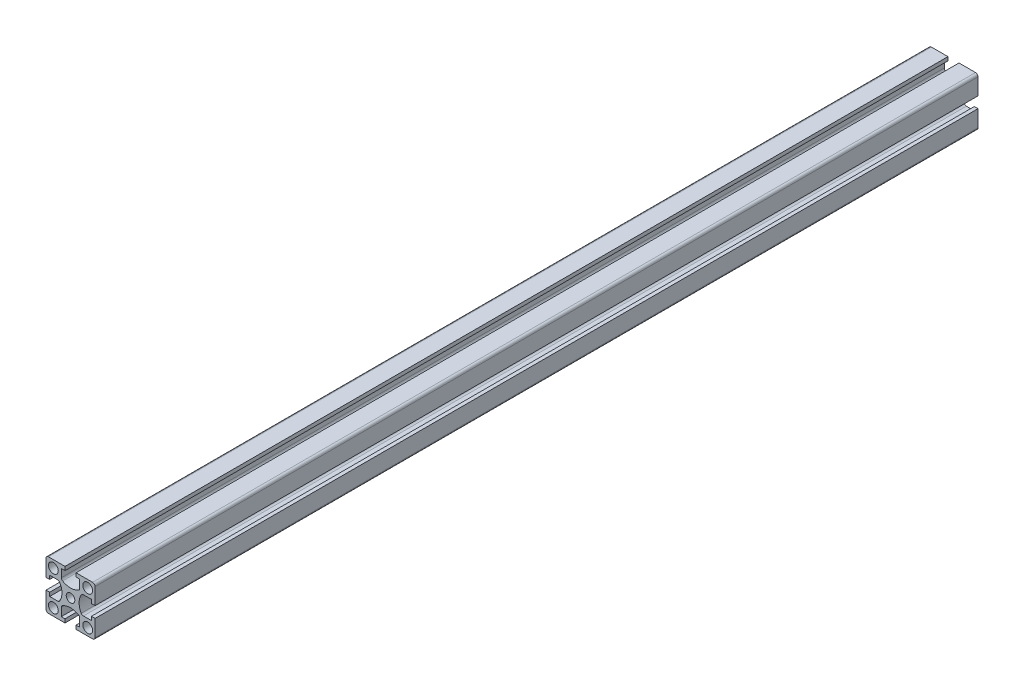
SolidWorks part; units mm, degrees
ref_plane "Front Plane" through (0, 0, 0) normal (0, 0, 1) x (1, 0, 0)
ref_plane "Top Plane" through (0, 0, 0) normal (0, 1, 0) x (1, 0, 0)
ref_plane "Right Plane" through (0, 0, 0) normal (1, 0, 0) x (0, 0, -1)
sketch "Sketch1" plane through (0, 0, 0) normal (0, 0, 1) x (1, 0, 0)
  line L64 (-12.5, 11.25) -> (-12.5, 2.8125)
  line L65 (-12.5, 2.8125) -> (-10.625, 2.8125)
  line L66 (-10.625, 2.8125) -> (-10.625, 4.6875)
  line L67 (-10.625, 4.6875) -> (-6.5461, 4.6875)
  line L68 (-6.5461, -4.6875) -> (-10.625, -4.6875)
  line L69 (-10.625, -4.6875) -> (-10.625, -2.8125)
  line L70 (-10.625, -2.8125) -> (-12.5, -2.8125)
  line L71 (-12.5, -2.8125) -> (-12.5, -11.25)
  line L72 (-11.25, -12.5) -> (-2.8125, -12.5)
  line L73 (-2.8125, -12.5) -> (-2.8125, -10.625)
  line L74 (-2.8125, -10.625) -> (-4.6875, -10.625)
  line L75 (-4.6875, -10.625) -> (-4.6875, -6.5461)
  line L76 (4.6875, -6.5461) -> (4.6875, -10.625)
  line L77 (4.6875, -10.625) -> (2.8125, -10.625)
  line L78 (2.8125, -10.625) -> (2.8125, -12.5)
  line L79 (2.8125, -12.5) -> (11.25, -12.5)
  line L80 (12.5, -11.25) -> (12.5, -2.8125)
  line L81 (12.5, -2.8125) -> (10.625, -2.8125)
  line L82 (10.625, -2.8125) -> (10.625, -4.6875)
  line L83 (10.625, -4.6875) -> (6.5461, -4.6875)
  line L84 (6.5461, 4.6875) -> (10.625, 4.6875)
  line L85 (10.625, 4.6875) -> (10.625, 2.8125)
  line L86 (10.625, 2.8125) -> (12.5, 2.8125)
  line L87 (12.5, 2.8125) -> (12.5, 11.25)
  line L88 (11.25, 12.5) -> (2.8125, 12.5)
  line L89 (2.8125, 12.5) -> (2.8125, 10.625)
  line L90 (2.8125, 10.625) -> (4.6875, 10.625)
  line L91 (4.6875, 10.625) -> (4.6875, 6.5461)
  line L92 (-4.6875, 6.5461) -> (-4.6875, 10.625)
  line L93 (-4.6875, 10.625) -> (-2.8125, 10.625)
  line L94 (-2.8125, 10.625) -> (-2.8125, 12.5)
  line L95 (-2.8125, 12.5) -> (-11.25, 12.5)
  circle A5 centre (-8.75, -8.75) radius 2.5
  circle A6 centre (8.75, -8.75) radius 2.5
  circle A7 centre (8.75, 8.75) radius 2.5
  circle A8 centre (0, 0) radius 2.1875
  circle A9 centre (-8.75, 8.75) radius 2.5
  arc A32 (-11.25, 12.5) -> (-12.5, 11.25) centre (-11.25, 11.25) ccw
  arc A33 (-5.4635, 4.0625) -> (-6.5461, 4.6875) centre (-6.5461, 3.4375) ccw
  arc A34 (-5.4635, -4.0625) -> (-5.4635, 4.0625) centre (-12.5, 0) ccw
  arc A35 (-6.5461, -4.6875) -> (-5.4635, -4.0625) centre (-6.5461, -3.4375) ccw
  arc A36 (-12.5, -11.25) -> (-11.25, -12.5) centre (-11.25, -11.25) ccw
  arc A37 (-4.0625, -5.4635) -> (-4.6875, -6.5461) centre (-3.4375, -6.5461) ccw
  arc A38 (4.0625, -5.4635) -> (-4.0625, -5.4635) centre (0, -12.5) ccw
  arc A39 (4.6875, -6.5461) -> (4.0625, -5.4635) centre (3.4375, -6.5461) ccw
  arc A40 (11.25, -12.5) -> (12.5, -11.25) centre (11.25, -11.25) ccw
  arc A41 (5.4635, -4.0625) -> (6.5461, -4.6875) centre (6.5461, -3.4375) ccw
  arc A42 (5.4635, 4.0625) -> (5.4635, -4.0625) centre (12.5, 0) ccw
  arc A43 (6.5461, 4.6875) -> (5.4635, 4.0625) centre (6.5461, 3.4375) ccw
  arc A44 (12.5, 11.25) -> (11.25, 12.5) centre (11.25, 11.25) ccw
  arc A45 (4.0625, 5.4635) -> (4.6875, 6.5461) centre (3.4375, 6.5461) ccw
  arc A46 (-4.0625, 5.4635) -> (4.0625, 5.4635) centre (0, 12.5) ccw
  arc A47 (-4.6875, 6.5461) -> (-4.0625, 5.4635) centre (-3.4375, 6.5461) ccw
extrude "Boss-Extrude1" add sketch "Sketch1" along normal blind 450
